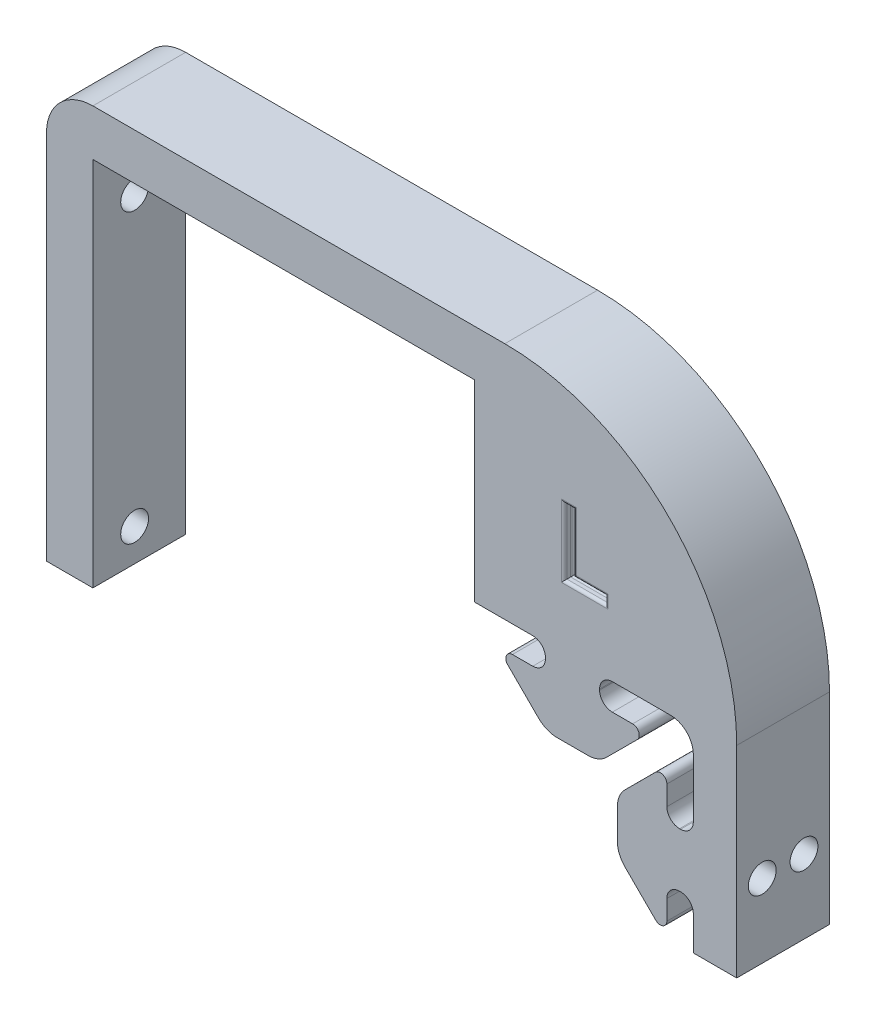
SolidWorks part; units mm, degrees
ref_plane "Front Plane" through (0, 0, 0) normal (0, 0, 1) x (1, 0, 0)
ref_plane "Top Plane" through (0, 0, 0) normal (0, 1, 0) x (1, 0, 0)
ref_plane "Right Plane" through (0, 0, 0) normal (1, 0, 0) x (0, 0, -1)
sketch "Sketch1" plane through (0, 0, 0) normal (0, 0, 1) x (1, 0, 0)
  line L0 (13.02, -7.9417) -> (17.7, -7.9417)
  line L1 (17.7, -7.9417) -> (17.7, 38.77)
  line L2 (17.7, 38.77) -> (-56.7, 38.77)
  line L3 (-14.4742, -8.23) -> (-67.0037, -8.23) construction
  line L4 (-19.4439, -8.23) -> (-19.4439, 33.77) construction
  line L5 (-10.5664, 13.02) -> (-10.5664, 33.77)
  line L6 (-10.5664, 33.77) -> (-51.7, 33.77)
  line L7 (-51.7, 33.77) -> (-51.7, -6.23)
  line L8 (-56.7, 38.77) -> (-56.7, -6.23)
  line L9 (-56.7, -6.23) -> (-51.7, -6.23)
  line L10 (12.7, -6.3331) -> (12.7, -7.9417) construction
  line L11 (13.02, -5.3171) -> (13.02, -4.2875)
  line L12 (11.651, -2.9185) -> (11.5392, -2.9185)
  line L13 (10.1702, -4.2875) -> (10.1702, -6.4021)
  line L14 (8.9631, -6.9029) -> (5.667, -3.6143)
  line L15 (4.8285, -1.5932) -> (4.8285, 1.5932)
  line L16 (5.667, 3.6143) -> (8.9631, 6.9029)
  line L17 (10.1702, 6.4021) -> (10.1702, 4.2875)
  line L18 (11.5392, 2.9185) -> (11.651, 2.9185)
  line L19 (13.02, 10.5773) -> (13.02, 4.2875)
  line L20 (6.3329, 13.02) -> (10.5626, 13.0198)
  line L22 (6.3329, 13.02) -> (4.2875, 13.02)
  line L23 (2.9185, 11.651) -> (2.9185, 11.5392)
  line L24 (4.2875, 10.1702) -> (6.4768, 10.1702)
  line L25 (6.981, 8.9509) -> (3.6723, 5.6497)
  line L26 (1.6558, 4.8158) -> (-1.6558, 4.8158)
  line L27 (-3.6723, 5.6497) -> (-6.981, 8.9509)
  line L28 (-6.4768, 10.1702) -> (-4.2875, 10.1702)
  line L29 (-2.9185, 11.5392) -> (-2.9185, 11.651)
  line L30 (-4.2875, 13.02) -> (-5.3171, 13.02)
  line L31 (-5.3171, 13.02) -> (-10.5664, 13.02)
  line L32 (13.02, -5.3171) -> (13.02, -7.9417)
  line L33 (13.02, -6.3331) -> (13.02, -7.9417) construction
  line L34 (13.02, 4.2875) -> (13.02, 5.3171) construction
  line L37 (5.3171, 13.02) -> (4.2875, 13.02) construction
  line L38 (-6.3331, 13.02) -> (-9.5504, 13.02) construction
  line L96 (12.7, -5.3171) -> (12.7, -4.2875) construction
  line L97 (11.651, -3.2385) -> (11.5392, -3.2385) construction
  line L98 (10.4902, -4.2875) -> (10.4902, -6.4021) construction
  line L99 (8.7371, -7.1294) -> (5.441, -3.8408) construction
  line L100 (4.5085, -1.5932) -> (4.5085, 1.5932) construction
  line L101 (5.441, 3.8408) -> (8.7371, 7.1294) construction
  line L102 (10.4902, 6.4021) -> (10.4902, 4.2875) construction
  line L103 (11.5392, 3.2385) -> (11.651, 3.2385) construction
  line L104 (12.7, 4.2875) -> (12.7, 5.3171) construction
  line L105 (12.7, 6.3331) -> (12.7, 9.5504) construction
  line L106 (9.5504, 12.7) -> (6.3331, 12.7) construction
  line L107 (5.3171, 12.7) -> (4.2875, 12.7) construction
  line L108 (3.2385, 11.651) -> (3.2385, 11.5392) construction
  line L109 (4.2875, 10.4902) -> (6.4768, 10.4902) construction
  line L110 (7.207, 8.7244) -> (3.8983, 5.4232) construction
  line L111 (1.6558, 4.4958) -> (-1.6558, 4.4958) construction
  line L112 (-3.8983, 5.4232) -> (-7.207, 8.7244) construction
  line L113 (-6.4768, 10.4902) -> (-4.2875, 10.4902) construction
  line L114 (-3.2385, 11.5392) -> (-3.2385, 11.651) construction
  line L115 (-4.2875, 12.7) -> (-5.3171, 12.7) construction
  line L116 (-6.3331, 12.7) -> (-9.5504, 12.7) construction
  arc A0 (13.02, -4.2875) -> (11.651, -2.9185) centre (11.651, -4.2875) ccw
  arc A1 (11.5392, -2.9185) -> (10.1702, -4.2875) centre (11.5392, -4.2875) ccw
  arc A2 (8.9631, -6.9029) -> (10.1702, -6.4021) centre (9.4628, -6.4021) ccw
  arc A3 (4.8285, -1.5932) -> (5.667, -3.6143) centre (7.6835, -1.5932) ccw
  arc A4 (5.667, 3.6143) -> (4.8285, 1.5932) centre (7.6835, 1.5932) ccw
  arc A5 (10.1702, 6.4021) -> (8.9631, 6.9029) centre (9.4628, 6.4021) ccw
  arc A6 (10.1702, 4.2875) -> (11.5392, 2.9185) centre (11.5392, 4.2875) ccw
  arc A7 (11.651, 2.9185) -> (13.02, 4.2875) centre (11.651, 4.2875) ccw
  arc A8 (4.2875, 13.02) -> (2.9185, 11.651) centre (4.2875, 11.651) ccw
  arc A9 (2.9185, 11.5392) -> (4.2875, 10.1702) centre (4.2875, 11.5392) ccw
  arc A10 (6.981, 8.9509) -> (6.4768, 10.1702) centre (6.4768, 9.4563) ccw
  arc A11 (1.6558, 4.8158) -> (3.6723, 5.6497) centre (1.6558, 7.6708) ccw
  arc A12 (-3.6723, 5.6497) -> (-1.6558, 4.8158) centre (-1.6558, 7.6708) ccw
  arc A13 (-6.4768, 10.1702) -> (-6.981, 8.9509) centre (-6.4768, 9.4563) ccw
  arc A14 (-4.2875, 10.1702) -> (-2.9185, 11.5392) centre (-4.2875, 11.5392) ccw
  arc A15 (-2.9185, 11.651) -> (-4.2875, 13.02) centre (-4.2875, 11.651) ccw
  arc A16 (13.02, 10.5773) -> (10.5626, 13.0198) centre (10.5918, 10.5918) ccw
  arc A17 (13.0198, 10.5625) -> (10.5626, 13.0198) centre (10.5918, 10.5918) ccw construction
  arc A114 (12.7, -5.3171) -> (12.7, -6.3331) centre (12.7, -5.8251) ccw construction
  arc A115 (12.7, -4.2875) -> (11.651, -3.2385) centre (11.651, -4.2875) ccw construction
  arc A116 (11.5392, -3.2385) -> (10.4902, -4.2875) centre (11.5392, -4.2875) ccw construction
  arc A117 (8.7371, -7.1294) -> (10.4902, -6.4021) centre (9.4628, -6.4021) ccw construction
  arc A118 (4.5085, -1.5932) -> (5.441, -3.8408) centre (7.6835, -1.5932) ccw construction
  arc A119 (5.441, 3.8408) -> (4.5085, 1.5932) centre (7.6835, 1.5932) ccw construction
  arc A120 (10.4902, 6.4021) -> (8.7371, 7.1294) centre (9.4628, 6.4021) ccw construction
  arc A121 (10.4902, 4.2875) -> (11.5392, 3.2385) centre (11.5392, 4.2875) ccw construction
  arc A122 (11.651, 3.2385) -> (12.7, 4.2875) centre (11.651, 4.2875) ccw construction
  arc A123 (12.7, 6.3331) -> (12.7, 5.3171) centre (12.7, 5.8251) ccw construction
  arc A124 (12.6998, 10.5664) -> (12.7, 9.5504) centre (12.7, 10.0584) ccw construction
  arc A125 (12.6998, 10.5664) -> (10.5664, 12.6998) centre (10.5918, 10.5918) ccw construction
  arc A126 (9.5504, 12.7) -> (10.5664, 12.6998) centre (10.0584, 12.7) ccw construction
  arc A127 (5.3171, 12.7) -> (6.3331, 12.7) centre (5.8251, 12.7) ccw construction
  arc A128 (4.2875, 12.7) -> (3.2385, 11.651) centre (4.2875, 11.651) ccw construction
  arc A129 (3.2385, 11.5392) -> (4.2875, 10.4902) centre (4.2875, 11.5392) ccw construction
  arc A130 (7.207, 8.7244) -> (6.4768, 10.4902) centre (6.4768, 9.4563) ccw construction
  arc A131 (1.6558, 4.4958) -> (3.8983, 5.4232) centre (1.6558, 7.6708) ccw construction
  arc A132 (-3.8983, 5.4232) -> (-1.6558, 4.4958) centre (-1.6558, 7.6708) ccw construction
  arc A133 (-6.4768, 10.4902) -> (-7.207, 8.7244) centre (-6.4768, 9.4563) ccw construction
  arc A134 (-4.2875, 10.4902) -> (-3.2385, 11.5392) centre (-4.2875, 11.5392) ccw construction
  arc A135 (-3.2385, 11.651) -> (-4.2875, 12.7) centre (-4.2875, 11.651) ccw construction
  arc A136 (-6.3331, 12.7) -> (-5.3171, 12.7) centre (-5.8251, 12.7) ccw construction
  arc A137 (-10.5664, 12.6998) -> (-9.5504, 12.7) centre (-10.0584, 12.7) ccw construction
  dimension "D1" = 47
  dimension "D2" = 74.4
  dimension "D3" = 5
  dimension "D4" = 5
  dimension "D5" = 40
  dimension "D6" = 5
  dimension "D8" = 0.32
  dimension "D7" = 6.2898
  dimension "D9" = 4.2297
  dimension "D10" = 20.75
extrude "Boss-Extrude1" add sketch "Sketch1" along normal blind 10
sketch "Sketch2" plane through (-56.7, 0, 0) normal (-1, 0, 0) x (0, 0, 1)
  line L1 (10, 38.77) -> (0, 38.77) construction
  line L2 (10, 29.3002) -> (10, -6.23) construction
  line L7 (5.5, 28.27) -> (5.5, -2.73) construction
  circle A0 centre (5.5, -2.73) radius 1.5
  circle A1 centre (5.5, 28.27) radius 1.5
  dimension "D3" = 3
  dimension "D4" = 3
  dimension "D1" = 4.5
  dimension "D2" = 31
  dimension "D5" = 10.5
extrude "Cut-Extrude1" cut sketch "Sketch2" against normal up to next
fillet "Fillet3" radius 5 1 edges at (-56.7, 38.77, 5)
sketch "Sketch3" plane through (17.7, 0, 0) normal (1, 0, 0) x (0, 0, -1)
  line L0 (-5, 1.5932) -> (-5, -1.5932) construction
  line L1 (-10, 0) -> (0, 0) construction
  line L4 (0, -1.5932) -> (0, 1.5932)
  line L5 (-10, -1.5932) -> (0, -1.5932)
  line L6 (-10, 1.5932) -> (-10, -1.5932)
  line L7 (0, 1.5932) -> (-10, 1.5932)
  line L12 (0, -1.5932) -> (0, 1.5932) construction
  line L13 (-10, -1.5932) -> (0, -1.5932) construction
  line L14 (-10, 1.5932) -> (-10, -1.5932) construction
  line L15 (0, 1.5932) -> (-10, 1.5932) construction
  circle A0 centre (-7.25, 0) radius 1.5
  circle A1 centre (-2.75, 0) radius 1.5
  point P12 (-10, 0)
  dimension "D2" = 3
  dimension "D3" = 2.25
  dimension "D1" = 0
extrude "Cut-Extrude2" cut sketch "Sketch3" against normal up to next
fillet "Fillet4" radius 25 1 edges at (17.7, 38.77, 5)
sketch "Sketch7" plane through (0, 0, 10) normal (0, 0, 1) x (1, 0, 0)
  text T0 "L" font "Arial" height in points 28
extrude "Cut-Extrude7" cut sketch "Sketch7" against normal blind 1
fillet "Fillet8" radius 0.3 12 edges at (-0.901, 23.4386, 9) (-0.3939, 27.0343, 9) (0.1132, 23.8535, 9) (1.8188, 20.6728, 9) (3.5244, 20.2579, 9) (1.3117, 19.843, 9) (1.3117, 19.843, 10) (3.5244, 20.2579, 10) (1.8188, 20.6728, 10) (0.1132, 23.8535, 10) (-0.3939, 27.0343, 10) (-0.901, 23.4386, 10)
